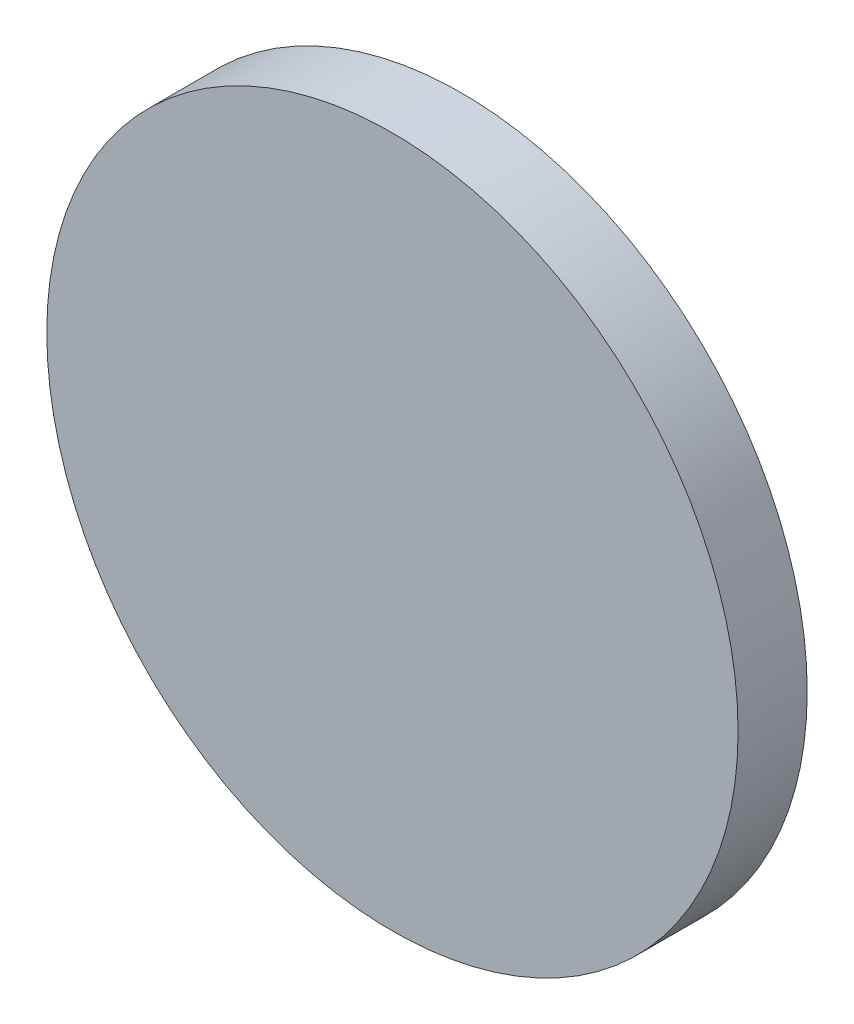
SolidWorks part; units mm, degrees
ref_plane "Front Plane" through (0, 0, 0) normal (0, 0, 1) x (1, 0, 0)
ref_plane "Top Plane" through (0, 0, 0) normal (0, 1, 0) x (1, 0, 0)
ref_plane "Right Plane" through (0, 0, 0) normal (1, 0, 0) x (0, 0, -1)
sketch "Sketch1" plane through (0, 0, 0) normal (0, 0, 1) x (1, 0, 0)
  circle A0 centre (0, 0) radius 50
  dimension "D1" = 100
extrude "Boss-Extrude1" add sketch "Sketch1" along normal blind 10
sketch "Sketch2" plane through (0, 0, 10) normal (0, 0, 1) x (1, 0, 0)
  line L0 (0, 0) -> (50, 0)
  circle A0 centre (0, 0) radius 50 construction
